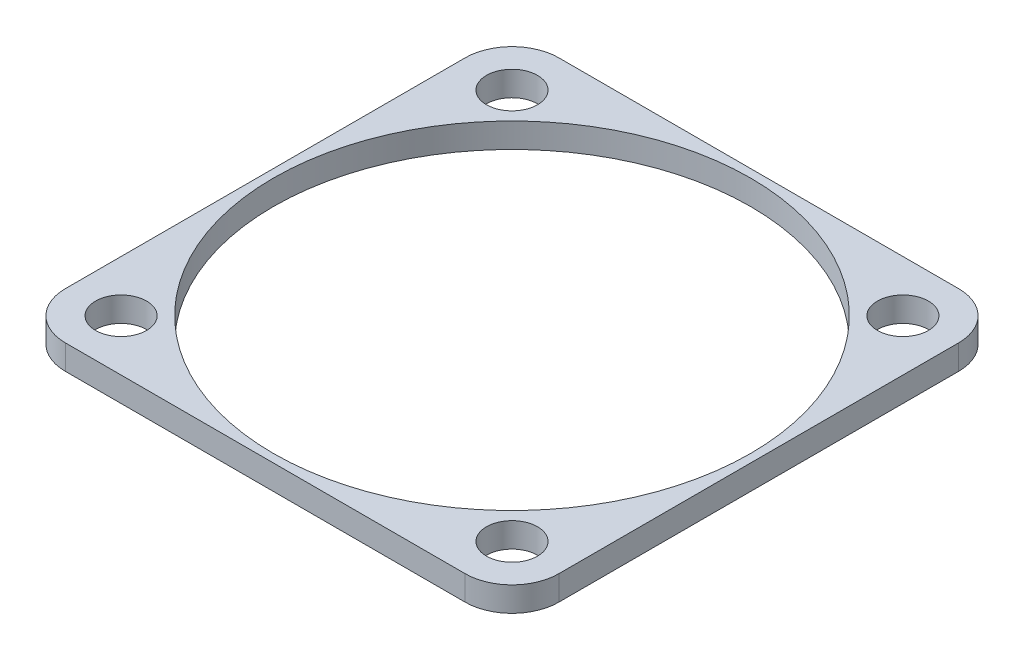
SolidWorks part; units mm, degrees
ref_plane "前视基准面" through (0, 0, 0) normal (0, 0, 1) x (1, 0, 0)
ref_plane "上视基准面" through (0, 0, 0) normal (0, 1, 0) x (1, 0, 0)
ref_plane "右视基准面" through (0, 0, 0) normal (1, 0, 0) x (0, 0, -1)
sketch "草图1" plane through (0, 0, 0) normal (0, 1, 0) x (1, 0, 0)
  line L0 (15, 15) -> (15, -15)
  line L1 (0, 0) -> (-11.8794, 11.8794) construction
  line L3 (-15, 15) -> (15, 15)
  line L4 (-15, -15) -> (15, -15)
  line L6 (-15, 15) -> (15, -15) construction
  line L7 (-15, -15) -> (15, 15) construction
  line L9 (-15, 15) -> (-15, -15)
  circle A0 centre (0, 0) radius 14.5
  circle A2 centre (-11.8794, 11.8794) radius 1.55
  circle A3 centre (11.8794, 11.8794) radius 1.55
  circle A4 centre (11.8794, -11.8794) radius 1.55
  circle A5 centre (-11.8794, -11.8794) radius 1.55
  point P6 (0, 0)
  point P15 (0, 0)
extrude "凸台-拉伸1" add sketch "草图1" along normal blind 1.5
fillet "圆角1" radius 2.85 4 edges at (15, 0.75, -15) (15, 0.75, 15) (-15, 0.75, 15) (-15, 0.75, -15)
